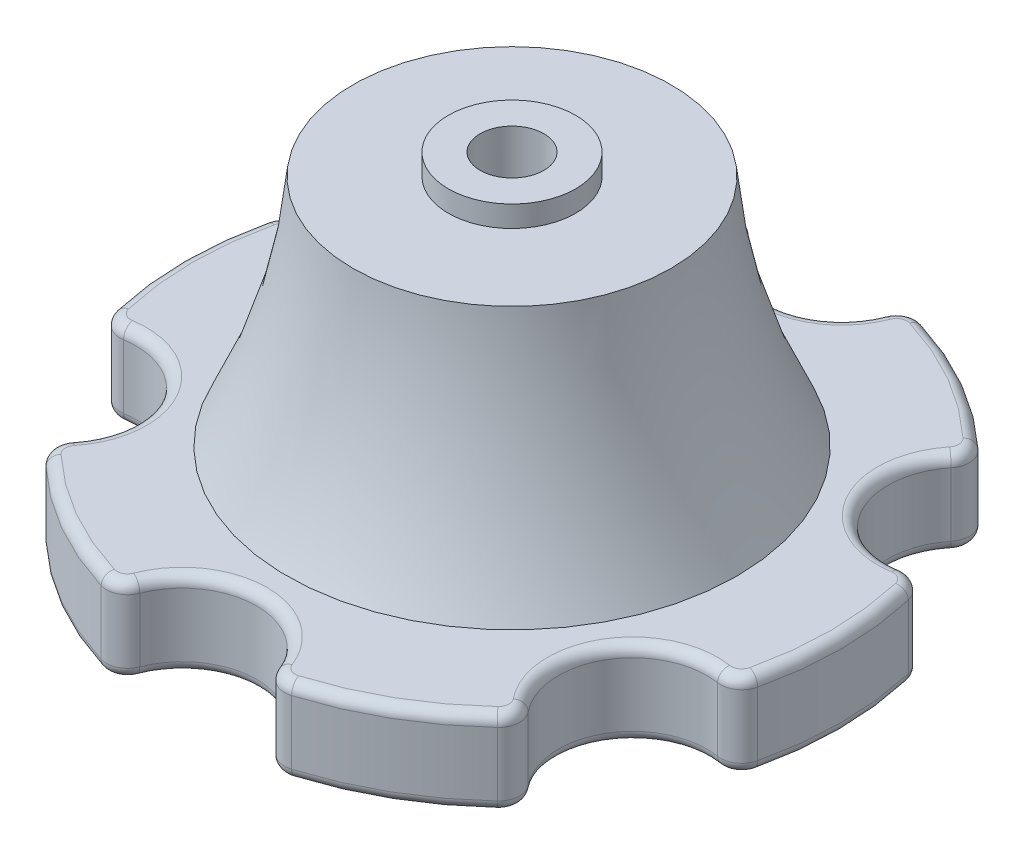
SolidWorks part; units mm, degrees
ref_plane "Спереди" through (0, 0, 0) normal (0, 0, 1) x (1, 0, 0)
ref_plane "Сверху" through (0, 0, 0) normal (0, 1, 0) x (1, 0, 0)
ref_plane "Справа" through (0, 0, 0) normal (1, 0, 0) x (0, 0, -1)
sketch "Эскиз1" plane through (0, 0, 0) normal (0, 1, 0) x (1, 0, 0)
  circle A0 centre (0, 0) radius 15.53 construction
  arc A1 (-3.4777, 15.1356) -> (3.4777, 15.1356) centre (0, 15.53) ccw
  arc A2 (3.4777, 15.1356) -> (11.369, 10.5796) centre (0, 0) cw
  arc A3 (11.369, 10.5796) -> (14.8467, 4.556) centre (13.4494, 7.765) ccw
  arc A4 (14.8467, 4.556) -> (14.8467, -4.556) centre (0, 0) cw
  arc A5 (14.8467, -4.556) -> (11.369, -10.5796) centre (13.4494, -7.765) ccw
  arc A6 (11.369, -10.5796) -> (3.4777, -15.1356) centre (0, 0) cw
  arc A7 (3.4777, -15.1356) -> (-3.4777, -15.1356) centre (0, -15.53) ccw
  arc A8 (-3.4777, -15.1356) -> (-11.369, -10.5796) centre (0, 0) cw
  arc A9 (-11.369, -10.5796) -> (-14.8467, -4.556) centre (-13.4494, -7.765) ccw
  arc A10 (-14.8467, -4.556) -> (-14.8467, 4.556) centre (0, 0) cw
  arc A11 (-14.8467, 4.556) -> (-11.369, 10.5796) centre (-13.4494, 7.765) ccw
  arc A12 (-11.369, 10.5796) -> (-3.4777, 15.1356) centre (0, 0) cw
  point P30 (0, 0)
  dimension "D1" = 3.5
  dimension "D3" = 6
  dimension "D2" = 15.53
extrude "Бобышка-Вытянуть1" add sketch "Эскиз1" along normal blind 15
sketch "Эскиз2" plane through (0, 0, 0) normal (0, 0, 1) x (1, 0, 0)
  line L0 (0, -1000) -> (0, 49000) construction
  line L1 (-15.6, 31) -> (-15.6, 4)
  line L2 (-15.6, 31) -> (-10.6, 31)
  line L3 (-15.6, 4) -> (-10.6, 4)
  line L4 (-3.4777, 0) -> (3.4777, 0) construction
  arc A0 (-10.6, 31) -> (-10.6, 4) centre (-37.3909, 17.5) cw
  dimension "D4" = 30
  dimension "D1" = 15.6
  dimension "D2" = 27
  dimension "D3" = 5
  dimension "D5" = 4
revolve "Вырез-Повернуть1" cut sketch "Эскиз2" angle 360 about L0
sketch "Эскиз3" plane through (0, 0, 0) normal (0, -1, 0) x (1, 0, 0)
  circle A0 centre (0, 0) radius 1.5
  dimension "D1" = 3
extrude "Вырез-Вытянуть1" cut sketch "Эскиз3" against normal blind 15
sketch "Эскиз4" plane through (0, 0, 0) normal (0, -1, 0) x (1, 0, 0)
  circle A0 centre (0, 0) radius 3
  dimension "D1" = 6
extrude "Вырез-Вытянуть2" cut sketch "Эскиз4" against normal blind 6
fillet "Скругление1" radius 1 12 edges at (-11.369, 2, 10.5796) (-3.4777, 2, 15.1356) (3.4777, 2, 15.1356) (11.369, 2, 10.5796) (14.8467, 2, 4.556) (14.8467, 2, -4.556) (11.369, 2, -10.5796) (-3.4777, 2, -15.1356) (3.4777, 2, -15.1356) (-11.369, 2, -10.5796) (-14.8467, 2, -4.556) (-14.8467, 2, 4.556)
fillet "Скругление2" radius 0.5 48 edges at (3.7592, 4, 14.8086) (0, 4, 12.03) (-3.7592, 4, 14.8086) (-7.765, 4, 13.4494) (-10.9451, 4, 10.6598) (-10.4183, 4, 6.015) (-14.7042, 4, 4.1488) (-15.53, 4, 0) (-14.7042, 4, -4.1488) (-10.4183, 4, -6.015) (-10.9451, 4, -10.6598) (-7.765, 4, -13.4494) (-3.7592, 4, -14.8086) (0, 4, -12.03) (3.7592, 4, -14.8086) (7.765, 4, -13.4494) (10.9451, 4, -10.6598) (10.4183, 4, -6.015) (14.7042, 4, -4.1488) (15.53, 4, 0) (14.7042, 4, 4.1488) (10.4183, 4, 6.015) (10.9451, 4, 10.6598) (-10.9451, 0, 10.6598) (-10.4183, 0, 6.015) (-14.7042, 0, 4.1488) (-15.53, 0, 0) (-14.7042, 0, -4.1488) (-10.4183, 0, -6.015) (-10.9451, 0, -10.6598) (-7.765, 0, -13.4494) (-3.7592, 0, -14.8086) (0, 0, -12.03) (3.7592, 0, -14.8086) (7.765, 0, -13.4494) (10.9451, 0, -10.6598) (10.4183, 0, -6.015) (14.7042, 0, -4.1488) (15.53, 0, 0) (14.7042, 0, 4.1488) (10.4183, 0, 6.015) (10.9451, 0, 10.6598) (7.765, 0, 13.4494) (3.7592, 0, 14.8086) (0, 0, 12.03) (-3.7592, 0, 14.8086) (7.765, 4, 13.4494) (-7.765, 0, 13.4494)
sketch "Эскиз5" plane through (0, 15, 0) normal (0, 1, 0) x (1, 0, 0)
  circle A0 centre (0, 0) radius 3
  circle A1 centre (0, 0) radius 1.5
  circle A3 centre (0, 0) radius 1.5 construction
  dimension "D1" = 6
extrude "Бобышка-Вытянуть2" add sketch "Эскиз5" along normal blind 1
